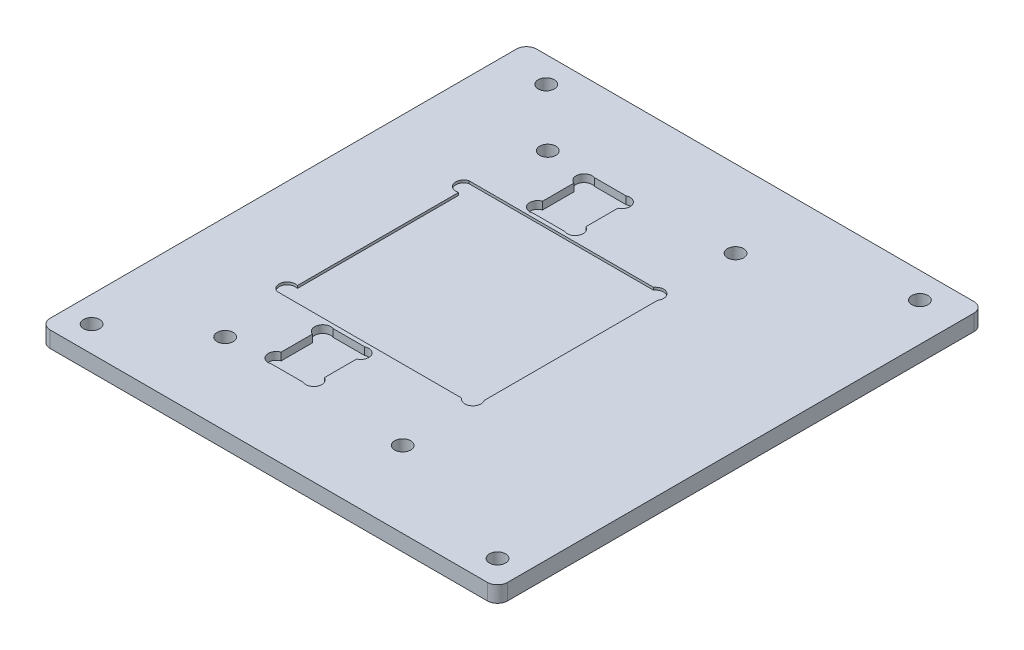
SolidWorks part; units mm, degrees
ref_plane "Front Plane" through (0, 0, 0) normal (0, 0, 1) x (1, 0, 0)
ref_plane "Top Plane" through (0, 0, 0) normal (0, 1, 0) x (1, 0, 0)
ref_plane "Right Plane" through (0, 0, 0) normal (1, 0, 0) x (0, 0, -1)
sketch "Sketch1" plane through (0, 0, 0) normal (0, 1, 0) x (1, 0, 0)
  line L1 (2, 0) -> (88.17, 0)
  line L2 (0, 2) -> (0, 93.89)
  line L3 (2, 95.89) -> (88.17, 95.89)
  line L4 (90.17, 2) -> (90.17, 93.89)
  arc A0 (0, 2) -> (2, 0) centre (2, 2) ccw
  arc A1 (90.17, 2) -> (88.17, 0) centre (88.17, 2) cw
  arc A2 (88.17, 95.89) -> (90.17, 93.89) centre (88.17, 93.89) cw
  arc A3 (2, 95.89) -> (0, 93.89) centre (2, 93.89) ccw
  point P7 (0, 0)
  point P12 (90.17, 95.89)
  point P15 (0, 95.89)
  dimension "D3" = 2
  dimension "D1" = 90.17
  dimension "D2" = 95.89
extrude "Boss-Extrude1" add sketch "Sketch1" along normal blind 3.175
sketch "Sketch2" plane through (0, 3.175, 0) normal (0, 1, 0) x (1, 0, 0)
  line L0 (-3.4925, 0) -> (3.4925, 0) construction
  line L1 (0, -3.4925) -> (0, 3.4925) construction
  line L4 (88.17, 95.89) -> (2, 95.89) construction
  circle A0 centre (5.08, 5.08) radius 1.5875
  circle A1 centre (8.9649, 90.81) radius 1.5875
  circle A2 centre (85.09, 5.08) radius 1.5875
  circle A3 centre (82.6249, 90.81) radius 1.5875
  circle A4 centre (20.45, 16.036) radius 1.59
  circle A5 centre (20.45, 79.636) radius 1.5875
  circle A6 centre (56.45, 80.636) radius 1.5875
  circle A7 centre (56.45, 15.036) radius 1.5875
  dimension "D2" = 3.175
  dimension "D4" = 3.175
  dimension "D6" = 3.175
  dimension "D9" = 3.175
  dimension "D12" = 3.18
  dimension "D15" = 3.175
  dimension "D19" = 3.175
  dimension "D21" = 3.175
  dimension "D1" = 5.08
  dimension "D3" = 5.08
  dimension "D5" = 85.73
  dimension "D8" = 80.01
  dimension "D7" = 5.08
  dimension "D10" = 73.66
  dimension "D11" = 5.08
  dimension "D13" = 10.956
  dimension "D14" = 15.37
  dimension "D16" = 63.6
  dimension "D17" = 36
  dimension "D18" = 1
  dimension "D20" = 65.6
  dimension "D22" = 36
extrude "Cut-Extrude1" cut sketch "Sketch2" against normal through all
sketch "Sketch3" plane through (0, 3.175, 0) normal (0, 1, 0) x (1, 0, 0)
  line L1 (17.787, 66.746) -> (54.1966, 66.746)
  line L2 (18.78, 63.7303) -> (18.78, 31.9417)
  line L3 (17.787, 28.926) -> (54.1966, 28.926)
  line L4 (56.81, 64.943) -> (56.81, 30.729)
  line L7 (88.17, 95.89) -> (2, 95.89) construction
  circle A0 centre (20.45, 79.636) radius 1.5875 construction
  arc A1 (17.787, 66.746) -> (18.78, 63.7303) centre (18.2835, 65.2381) ccw
  circle A2 centre (56.45, 80.636) radius 1.5875 construction
  arc A3 (56.81, 64.943) -> (54.1966, 66.746) centre (55.5033, 65.8445) ccw
  arc A4 (54.1966, 28.926) -> (56.81, 30.729) centre (55.5033, 29.8275) ccw
  arc A5 (18.78, 31.9417) -> (17.787, 28.926) centre (18.2835, 30.4339) ccw
  point P8 (13.5708, 28.6573)
  point P11 (16.4471, 32.0605)
  point P12 (18.4483, 28.926)
  point P13 (16.7, 31.179)
  point P22 (0, 0)
  point P23 (16.7, 63.7629)
  dimension "D4" = 3.175
  dimension "D9" = 3.175
  dimension "D5" = 1.5875
  dimension "D11" = 1.5875
  dimension "D12" = 1.5875
  dimension "D2" = 1.5875
  dimension "D6" = 29.144
  dimension "D8" = 3.175
  dimension "D10" = 3.175
  dimension "D3" = 37.82
  dimension "D13" = 38.03
  dimension "D14" = 1.67
  dimension "D7" = 0.36
extrude "Cut-Extrude2" cut sketch "Sketch3" against normal blind 0.5
sketch "Sketch4" plane through (0, 3.175, 0) normal (0, 1, 0) x (1, 0, 0)
  line L0 (17.787, 28.926) -> (54.1966, 28.926) construction
  line L1 (29.6388, 28.126) -> (35.8612, 28.126)
  line L2 (28.55, 25.1435) -> (28.55, 18.9885)
  line L3 (29.6388, 16.006) -> (35.8612, 16.006)
  line L4 (37.17, 25.2333) -> (37.17, 18.8987)
  line L5 (37.17, 76.7533) -> (37.17, 70.4187)
  line L6 (29.6388, 79.646) -> (35.8612, 79.646)
  line L7 (28.55, 76.6635) -> (28.55, 70.5085)
  line L8 (29.6388, 67.526) -> (35.8612, 67.526)
  circle A0 centre (20.45, 16.036) radius 1.59 construction
  arc A1 (29.6388, 28.126) -> (28.55, 25.1435) centre (29.0944, 26.6348) ccw
  arc A2 (37.17, 25.2333) -> (35.8612, 28.126) centre (36.5156, 26.6796) ccw
  arc A3 (28.55, 18.9885) -> (29.6388, 16.006) centre (29.0944, 17.4972) ccw
  arc A4 (35.8612, 16.006) -> (37.17, 18.8987) centre (36.5156, 17.4524) ccw
  arc A5 (35.8612, 67.526) -> (37.17, 70.4187) centre (36.5156, 68.9724) ccw
  arc A6 (37.17, 76.7533) -> (35.8612, 79.646) centre (36.5156, 78.1996) ccw
  arc A7 (29.6388, 79.646) -> (28.55, 76.6635) centre (29.0944, 78.1548) ccw
  arc A8 (28.55, 70.5085) -> (29.6388, 67.526) centre (29.0944, 69.0172) ccw
  point P17 (34.27, 25.6586)
  point P29 (39.3251, 28.126)
  point P30 (28.33, 25.2333)
  dimension "D1" = 3.175
  dimension "D5" = 1.5875
  dimension "D10" = 3.175
  dimension "D6" = 1.5875
  dimension "D7" = 1.5875
  dimension "D8" = 1.5875
  dimension "D9" = 0.8
  dimension "D11" = 12.12
  dimension "D12" = 2.8927
  dimension "D2" = 8.62
  dimension "D3" = 3.175
  dimension "D13" = 3.175
  dimension "D4" = 8.1
  dimension "D14" = 2
extrude "Cut-Extrude3" cut sketch "Sketch4" against normal blind 1.5
equation "\"PlateThickness\" = 0.125in"
equation "\"D1@Boss-Extrude1\"=\"PlateThickness\""
equation "\"HoleDistance\"=5.08"
equation "\"D3@Sketch2\"=\"HoleDistance\""
equation "\"BitSize\"= 0.125in"
equation "\"AttachmentBitSize\"= 0.125in"
equation "\"D2@Sketch2\"=\"AttachmentBitSize\""
equation "\"D4@Sketch2\"=\"AttachmentBitSize\""
equation "\"D6@Sketch2\"=\"AttachmentBitSize\""
equation "\"D9@Sketch2\"=\"AttachmentBitSize\""
equation "\"D11@Sketch2\"=\"HoleDistance\""
equation "\"D12@Sketch2\"=3.18"
equation "\"D15@Sketch2\"=\"AttachmentBitSize\""
equation "\"D19@Sketch2\"=\"AttachmentBitSize\""
equation "\"D21@Sketch2\"=\"AttachmentBitSize\""
equation "\"D8@Sketch3\"=\"AttachmentBitSize\""
equation "\"D4@Sketch3\"=\"AttachmentBitSize\""
equation "\"D9@Sketch3\"=\"AttachmentBitSize\""
equation "\"D10@Sketch3\"=\"AttachmentBitSize\""
equation "\"D5@Sketch3\"=\"AttachmentBitSize\" / 2"
equation "\"D11@Sketch3\"=\"AttachmentBitSize\" / 2"
equation "\"D12@Sketch3\"=\"AttachmentBitSize\" / 2"
equation "\"D2@Sketch3\"=\"AttachmentBitSize\" / 2"
equation "\"D5@Sketch4\"=\"AttachmentBitSize\" / 2"
equation "\"D6@Sketch4\"=\"AttachmentBitSize\" / 2"
equation "\"D7@Sketch4\"=\"AttachmentBitSize\" / 2"
equation "\"D8@Sketch4\"= \"AttachmentBitSize\" / 2"
equation "\"D1@Sketch4\"=\"AttachmentBitSize\""
equation "\"D10@Sketch4\"=\"AttachmentBitSize\""
equation "\"D3@Sketch4\"=\"AttachmentBitSize\""
equation "\"D13@Sketch4\"=\"AttachmentBitSize\""
